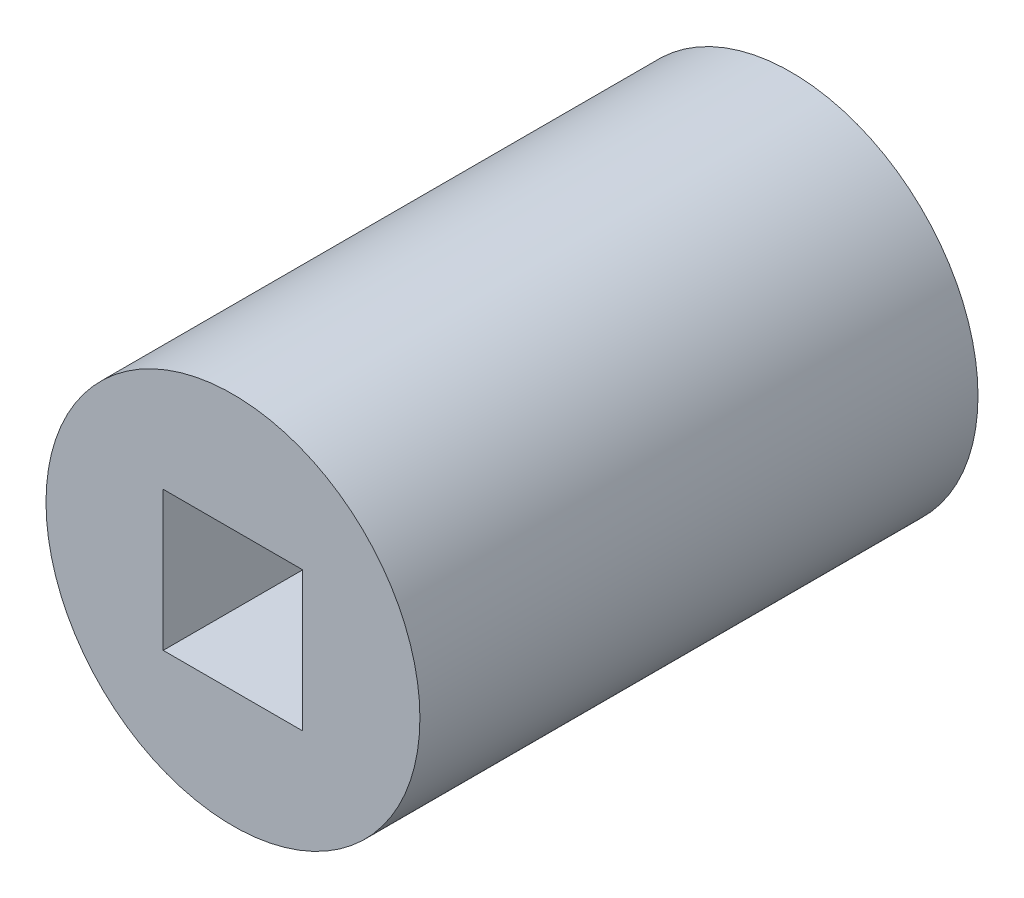
SolidWorks part; units mm, degrees
ref_plane "Front Plane" through (0, 0, 0) normal (0, 0, 1) x (1, 0, 0)
ref_plane "Top Plane" through (0, 0, 0) normal (0, 1, 0) x (1, 0, 0)
ref_plane "Right Plane" through (0, 0, 0) normal (1, 0, 0) x (0, 0, -1)
sketch "Sketch1" plane through (0, 0, 0) normal (0, 0, 1) x (1, 0, 0)
  circle A0 centre (0, 0) radius 3.35
  dimension "D1" = 6.7
extrude "Boss-Extrude1" add sketch "Sketch1" along normal blind 10
sketch "Sketch2" plane through (0, 0, 10) normal (0, 0, 1) x (1, 0, 0)
  line L1 (-1.25, 1.25) -> (1.25, 1.25)
  line L2 (-1.25, 1.25) -> (-1.25, -1.25)
  line L3 (-1.25, -1.25) -> (1.25, -1.25)
  line L4 (1.25, 1.25) -> (1.25, -1.25)
  line L5 (-1.25, 1.25) -> (1.25, -1.25) construction
  line L6 (-1.25, -1.25) -> (1.25, 1.25) construction
  point P0 (0, 0)
  dimension "D1" = 2.5
  dimension "D2" = 2.5
extrude "Cut-Extrude1" cut sketch "Sketch2" against normal blind 5
sketch "Sketch3" plane through (0, 0, 0) normal (0, 0, -1) x (-1, 0, 0)
  circle A0 centre (0, 0) radius 2.35
  dimension "D1" = 4.7
extrude "Cut-Extrude2" cut sketch "Sketch3" against normal blind 3
sketch "Sketch4" plane through (0, 0, 3) normal (0, 0, -1) x (-1, 0, 0)
  circle A0 centre (0, 0) radius 1
  dimension "D1" = 2
extrude "Cut-Extrude3" cut sketch "Sketch4" against normal blind 3
